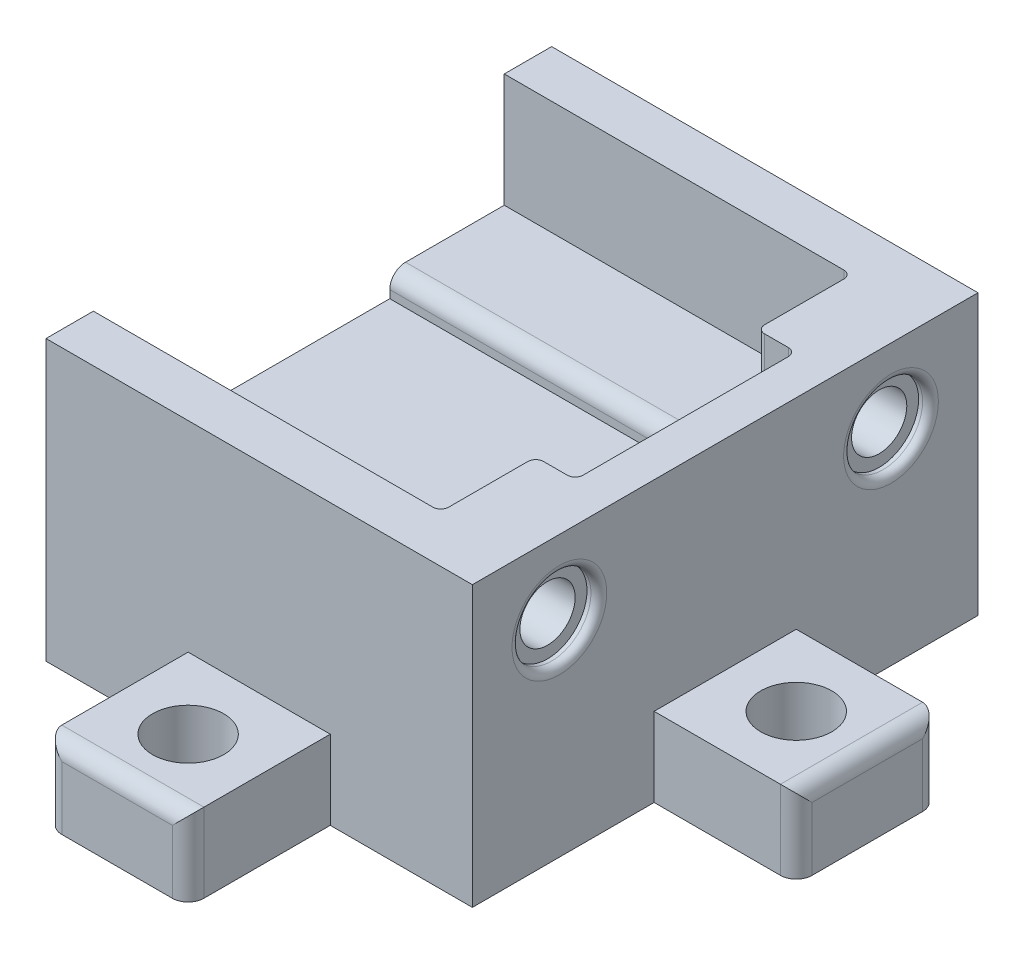
SolidWorks part; units mm, degrees
ref_plane "Front" through (0, 0, 0) normal (0, 0, 1) x (1, 0, 0)
ref_plane "Top" through (0, 0, 0) normal (0, 1, 0) x (1, 0, 0)
ref_plane "Right" through (0, 0, 0) normal (1, 0, 0) x (0, 0, -1)
sketch "Sketch1" plane through (0, 0, 0) normal (1, 0, 0) x (0, 0, -1)
  line L0 (-13.0089, 0) -> (13.0089, 0)
  line L1 (13.0089, 0) -> (13.0089, 10.5)
  line L2 (13.0089, 10.5) -> (5.7589, 10.5)
  line L3 (5.7589, 10.5) -> (5.7589, 9)
  line L4 (5.7589, 9) -> (-5.7589, 9)
  line L5 (-5.7589, 9) -> (-5.7589, 10.5)
  line L6 (-5.7589, 10.5) -> (-13.0089, 10.5)
  line L7 (-13.0089, 10.5) -> (-13.0089, 0)
  dimension "D1" = 10.5
  dimension "D2" = 7.25
  dimension "D3" = 26.0178
  dimension "D4" = 1.5
extrude "Boss-Extrude1" add sketch "Sketch1" along normal mid plane 22
sketch "Sketch3" plane through (0, 0, 0) normal (0, -1, 0) x (1, 0, 0)
  line L1 (-11, -13.0089) -> (11, -13.0089)
  line L2 (-11, -13.0089) -> (-11, -16.0089)
  line L3 (-11, -16.0089) -> (11, -16.0089)
  line L4 (11, -13.0089) -> (11, -16.0089)
  line L5 (-11, 13.0089) -> (11, 13.0089)
  line L6 (-11, 13.0089) -> (-11, 16.0089)
  line L7 (-11, 16.0089) -> (11, 16.0089)
  line L8 (11, 13.0089) -> (11, 16.0089)
  dimension "D1" = 3
  dimension "D2" = 22
  dimension "D3" = 3
  dimension "D4" = 22
extrude "Boss-Extrude2" add sketch "Sketch3" against normal blind 17.7
sketch "Sketch4" plane through (11, 0, 0) normal (1, 0, 0) x (0, 0, -1)
  line L0 (0, 0) -> (0, 17.7) construction
  line L1 (-16.0089, 0) -> (16.0089, 0) construction
  line L2 (-8.8, 17.7) -> (-16.0089, 17.7)
  line L3 (-16.0089, 17.7) -> (-16.0089, 0) construction
  line L4 (-16.0089, 17.7) -> (-16.0089, 0)
  line L5 (-16.0089, 0) -> (16.0089, 0)
  line L6 (16.0089, 0) -> (16.0089, 17.7)
  line L7 (16.0089, 17.7) -> (16.0089, 0) construction
  line L8 (16.0089, 17.7) -> (-8.8, 17.7)
extrude "Boss-Extrude3" add sketch "Sketch4" along normal blind 5
sketch "Sketch5" plane through (16, 0, 0) normal (1, 0, 0) x (0, 0, -1)
  line L0 (-16.0089, 13) -> (-10.5, 13) construction
  line L1 (-16.0089, 17.7) -> (-16.0089, 0) construction
  line L2 (-10.5, 13) -> (-10.5, 0) construction
  line L3 (-16.0089, 0) -> (16.0089, 0) construction
  line L4 (0, 0) -> (0, 17.7) construction
  line L5 (16.0089, 17.7) -> (-16.0089, 17.7) construction
  circle A0 centre (-10.5, 13) radius 1.75
  circle A1 centre (10.5, 13) radius 1.75
  dimension "D3" = 3.5
  dimension "D1" = 5.5089
  dimension "D2" = 13
extrude "Cut-Extrude1" cut sketch "Sketch5" against normal through all
sketch "Sketch6" plane through (0, 0, 0) normal (0, -1, 0) x (1, 0, 0)
  line L0 (16, 16.0089) -> (16, -16.0089) construction
  line L5 (0, 0) -> (16, 0) construction
  line L13 (16, 4.5) -> (25, 4.5)
  line L15 (7, 16.0089) -> (-2, 16.0089)
  line L20 (7, 16.0089) -> (7, 25.0089)
  line L21 (7, 25.0089) -> (-2, 25.0089)
  line L22 (-2, 16.0089) -> (-2, 25.0089)
  line L23 (16, 4.5) -> (16, -4.5)
  line L24 (16, -4.5) -> (25, -4.5)
  line L25 (25, 4.5) -> (25, -4.5)
  line L26 (16, 16.0089) -> (-11, 16.0089) construction
  point P12 (2.5, 16.0089)
  dimension "D1" = 9
  dimension "D2" = 9
  dimension "D3" = 9
  dimension "D4" = 9
extrude "Boss-Extrude4" add sketch "Sketch6" against normal blind 5
sketch "Sketch7" plane through (0, 5, 0) normal (0, 1, 0) x (1, 0, 0)
  line L0 (25, 0) -> (7, 0) construction
  line L2 (2.5, -16.0089) -> (2.5, -25.0089) construction
  line L3 (20.5, 4.5) -> (20.5, -4.5) construction
  line L4 (-2, -16.0089) -> (7, -16.0089) construction
  line L5 (7, -25.0089) -> (-2, -25.0089) construction
  line L7 (7, -4.5) -> (7, 4.5) construction
  line L8 (25, 4.5) -> (25, -4.5) construction
  line L9 (-2, -20.5089) -> (7, -20.5089) construction
  line L10 (16, 4.5) -> (25, 4.5) construction
  line L11 (25, -4.5) -> (16, -4.5) construction
  line L12 (-2, -25.0089) -> (-2, -16.0089) construction
  line L15 (7, -16.0089) -> (7, -25.0089) construction
  circle A0 centre (20.5, 0) radius 2.25
  circle A1 centre (2.5, -20.5089) radius 2.25
  point P5 (7, 0)
  point P11 (25, 0)
  point P23 (2.5, -20.5089)
  point P29 (20.5, 4.5)
  dimension "D1" = 4.5
extrude "Cut-Extrude2" cut sketch "Sketch7" against normal through all
fillet "Fillet1" radius 1 8 edges at (2.5, 5, 25.0089) (0, 10.5, 5.7589) (0, 10.5, -5.7589) (25, 5, 0) (25, 2.5, 4.5) (25, 2.5, -4.5) (7, 2.5, 25.0089) (-2, 2.5, 25.0089)
sketch "Sketch8" plane through (16, 0, 0) normal (1, 0, 0) x (0, 0, -1)
  circle A0 centre (-10.5, 13) radius 2.5
  circle A1 centre (10.5, 13) radius 2.5
  dimension "D1" = 5
extrude "Cut-Extrude3" cut sketch "Sketch8" against normal blind 0.75
fillet "Fillet2" radius 0.5 2 edges at (16, 13, -13) (16, 13, 8)
sketch "Sketch10" plane through (11, 0, 0) normal (-1, 0, 0) x (0, 0, 1)
  line L0 (-13.0089, 17.7) -> (13.0089, 17.7) construction
  line L1 (-7, 10.5) -> (7, 10.5)
  line L2 (-7, 10.5) -> (-7, 17.7)
  line L3 (-7, 17.7) -> (7, 17.7)
  line L4 (7, 10.5) -> (7, 17.7)
  line L5 (6.7589, 10.5) -> (13.0089, 10.5) construction
  circle A0 centre (-10.5, 13) radius 1.75 construction
  circle A1 centre (10.5, 13) radius 1.75 construction
  point P6 (7.7102, 10.5)
  point P9 (0, 0)
  dimension "D1" = 3.5
  dimension "D2" = 3.5
extrude "Cut-Extrude4" cut sketch "Sketch10" against normal blind 2.5
fillet "Fillet3" radius 0.5 6 edges at (11, 14.1, 13.0089) (11, 14.1, -13.0089) (11, 14.1, 7) (11, 14.1, -7) (13.5, 14.1, 7) (13.5, 14.1, -7)
